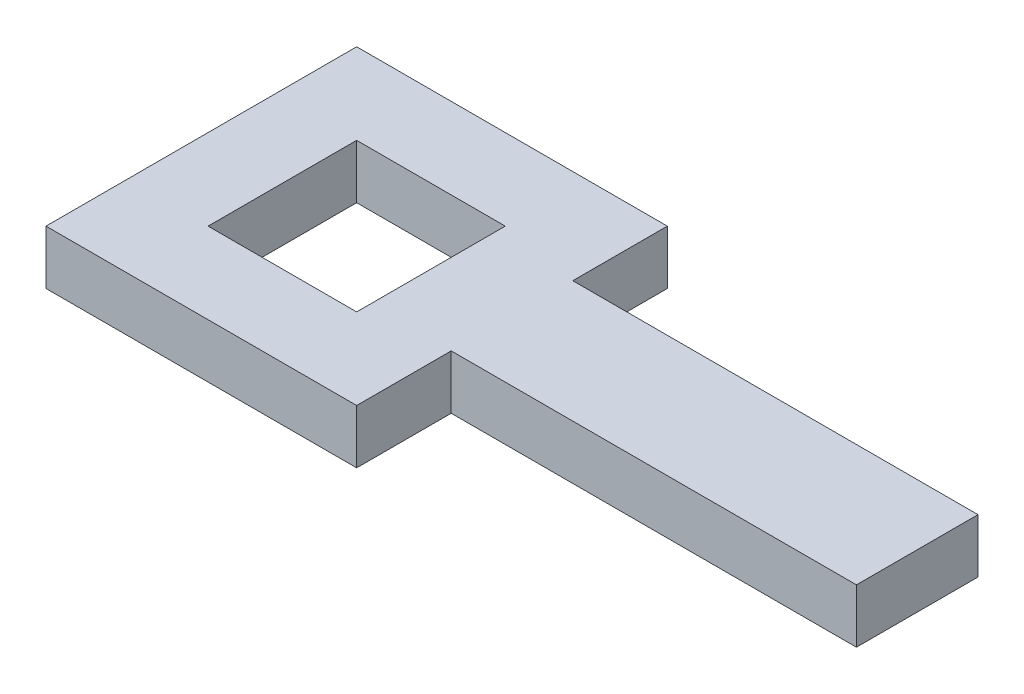
SolidWorks part; units mm, degrees
ref_plane "Front Plane" through (0, 0, 0) normal (0, 0, 1) x (1, 0, 0)
ref_plane "Top Plane" through (0, 0, 0) normal (0, 1, 0) x (1, 0, 0)
ref_plane "Right Plane" through (0, 0, 0) normal (1, 0, 0) x (0, 0, -1)
sketch "Sketch1" plane through (0, 0, 0) normal (0, 1, 0) x (1, 0, 0)
  line L1 (-11.8188, 11.7277) -> (11.1812, 11.7277)
  line L2 (-11.8188, 11.7277) -> (-11.8188, -11.2723)
  line L3 (-11.8188, -11.2723) -> (11.1812, -11.2723)
  line L4 (11.1812, 11.7277) -> (11.1812, -11.2723)
  dimension "D1" = 23
  dimension "D2" = 23
extrude "Boss-Extrude1" add sketch "Sketch1" along normal blind 4
sketch "Sketch2" plane through (0, 4, 0) normal (0, 1, 0) x (1, 0, 0)
  line L0 (-11.8188, 11.7277) -> (-11.8188, -11.2723) construction
  line L1 (-5.8188, 5.7277) -> (5.1812, 5.7277)
  line L2 (-5.8188, 5.7277) -> (-5.8188, -5.2723)
  line L3 (-5.8188, -5.2723) -> (5.1812, -5.2723)
  line L4 (5.1812, 5.7277) -> (5.1812, -5.2723)
  line L5 (11.1812, -11.2723) -> (11.1812, 11.7277) construction
  line L6 (11.1812, 11.7277) -> (-11.8188, 11.7277) construction
  line L7 (-11.8188, -11.2723) -> (11.1812, -11.2723) construction
  dimension "D1" = 6
  dimension "D2" = 6
  dimension "D3" = 6
  dimension "D4" = 6
extrude "Cut-Extrude1" cut sketch "Sketch2" against normal blind 4
sketch "Sketch3" plane through (11.1812, 0, 0) normal (1, 0, 0) x (0, 0, -1)
  line L0 (-11.2723, 4) -> (11.7277, 4) construction
  line L1 (-4.2723, 4) -> (4.7277, 4)
  line L2 (-4.2723, 4) -> (-4.2723, 0)
  line L3 (-4.2723, 0) -> (4.7277, 0)
  line L4 (4.7277, 4) -> (4.7277, 0)
  line L5 (-11.2723, 0) -> (11.7277, 0) construction
  line L6 (-11.2723, 4) -> (-11.2723, 0) construction
  line L7 (11.7277, 4) -> (11.7277, 0) construction
  dimension "D1" = 7
  dimension "D2" = 7
extrude "Boss-Extrude2" add sketch "Sketch3" along normal blind 30
